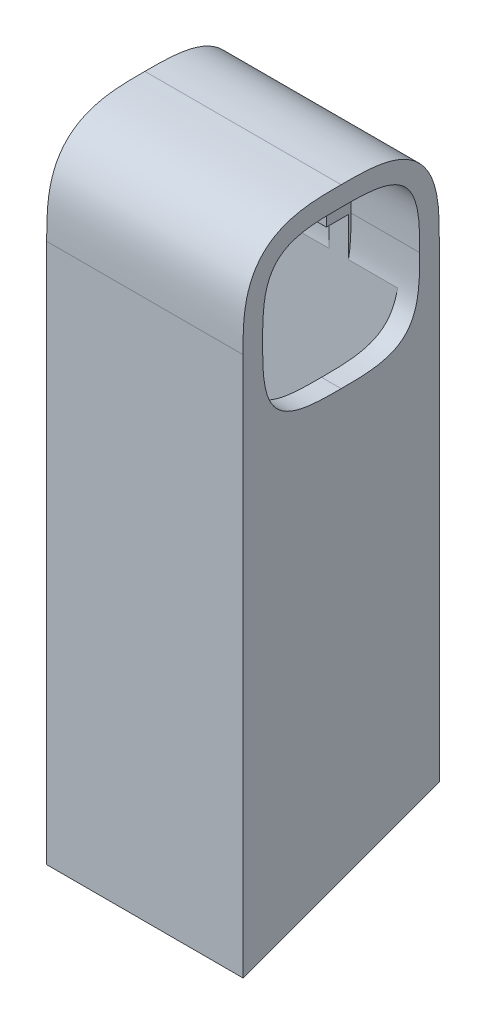
SolidWorks part; units mm, degrees
ref_plane "前视基准面" through (0, 0, 0) normal (0, 0, 1) x (1, 0, 0)
ref_plane "上视基准面" through (0, 0, 0) normal (0, 1, 0) x (1, 0, 0)
ref_plane "右视基准面" through (0, 0, 0) normal (1, 0, 0) x (0, 0, -1)
other "Configuration Table"
sketch "草图1" plane through (0, 0, 0) normal (1, 0, 0) x (0, 0, -1)
  line L4 (0, 0) -> (0, 12.2063) construction
  line L6 (-10, 0) -> (-10, -55)
  line L8 (10, 0) -> (10, -47.7206)
  line L9 (-10, 0) -> (10, 0) construction
  line L10 (-10, -55) -> (10, -47.7206)
  spline S0 degree 4 poles (-1.0181, 10.0032) (-0.7725, 10.0013) (-0.4941, 10.0001) (-0.0263, 9.9999) (0.7234, 10.0003) (1.6031, 9.9942) (2.5936, 9.9522) (3.5304, 9.8651) (4.2846, 9.7393) (4.9221, 9.5926) (5.4228, 9.4446) (5.9166, 9.2643) (6.3946, 9.0487) (6.8546, 8.7957) (7.2712, 8.5176) (7.6286, 8.2324) (7.9468, 7.9356) (8.2427, 7.6166) (8.5281, 7.2568) (8.806, 6.8375) (9.0575, 6.3768) (9.2717, 5.8978) (9.4508, 5.4047) (9.5975, 4.901) (9.7444, 4.2634) (9.8884, 3.3683) (9.9835, 2.2038) (9.9997, 1.1675) (10.0003, 0.3923) (10, 0) knots 0 0 0 0 0 0.048706 0.055984 0.114683 0.173382 0.232082 0.289096 0.318446 0.347795 0.377145 0.406494 0.435844 0.465193 0.494543 0.518534 0.538101 0.562555 0.591905 0.621254 0.650602 0.679953 0.709301 0.738647 0.767998 0.826406 0.91214 1 1 1 1 1 construction
  spline S1 degree 4 poles (0, 10) (0.2475, 10) (0.7583, 10) (1.6031, 9.9942) (2.5936, 9.9522) (3.5304, 9.8651) (4.2846, 9.7393) (4.9221, 9.5926) (5.4228, 9.4446) (5.9166, 9.2643) (6.3946, 9.0487) (6.8546, 8.7957) (7.2712, 8.5176) (7.6286, 8.2324) (7.9468, 7.9356) (8.2427, 7.6166) (8.5281, 7.2568) (8.806, 6.8375) (9.0575, 6.3768) (9.2717, 5.8978) (9.4508, 5.4047) (9.5975, 4.901) (9.7444, 4.2634) (9.8884, 3.3683) (9.9835, 2.2038) (9.9997, 1.1675) (10.0003, 0.3923) (10, 0) knots 0.055984 0.055984 0.055984 0.055984 0.055984 0.114683 0.173382 0.232082 0.289096 0.318446 0.347795 0.377145 0.406494 0.435844 0.465193 0.494543 0.518534 0.538101 0.562555 0.591905 0.621254 0.650602 0.679953 0.709301 0.738647 0.767998 0.826406 0.91214 1 1 1 1 1
  spline S2 degree 4 poles (0, 10) (-0.2475, 10) (-0.7583, 10) (-1.6031, 9.9942) (-2.5936, 9.9522) (-3.5304, 9.8651) (-4.2846, 9.7393) (-4.9221, 9.5926) (-5.4228, 9.4446) (-5.9166, 9.2643) (-6.3946, 9.0487) (-6.8546, 8.7957) (-7.2712, 8.5176) (-7.6286, 8.2324) (-7.9468, 7.9356) (-8.2427, 7.6166) (-8.5281, 7.2568) (-8.806, 6.8375) (-9.0575, 6.3768) (-9.2717, 5.8978) (-9.4508, 5.4047) (-9.5975, 4.901) (-9.7444, 4.2634) (-9.8884, 3.3683) (-9.9835, 2.2038) (-9.9997, 1.1675) (-10.0003, 0.3923) (-10, 0) knots 0.055984 0.055984 0.055984 0.055984 0.055984 0.114683 0.173382 0.232082 0.289096 0.318446 0.347795 0.377145 0.406494 0.435844 0.465193 0.494543 0.518534 0.538101 0.562555 0.591905 0.621254 0.650602 0.679953 0.709301 0.738647 0.767998 0.826406 0.91214 1 1 1 1 1
  dimension "D1" = 20
  dimension "D2" = 55
  dimension "D3" = 70
extrude "凸台-拉伸1" add sketch "草图1" along normal blind 20
sketch "草图4" plane through (0, 0, 0) normal (-1, 0, 0) x (0, 0, 1)
  line L3 (-8, 0.0015) -> (8, 0.0015) construction
  spline S5 degree 3 poles (0, -7.997) (0.1658, -7.997) (0.3341, -7.997) (0.6769, -7.996) (0.8514, -7.995) (1.1985, -7.9913) (1.3702, -7.9885) (1.7022, -7.9803) (1.8625, -7.9748) (2.1776, -7.9606) (2.3333, -7.9517) (2.6457, -7.9296) (2.8024, -7.9164) (3.1102, -7.8854) (3.2605, -7.8675) (3.552, -7.8267) (3.6932, -7.8037) (3.9751, -7.751) (4.1165, -7.7212) (4.3885, -7.6563) (4.5182, -7.6213) (4.7735, -7.5439) (4.8994, -7.5014) (5.1417, -7.4103) (5.2579, -7.3617) (5.8205, -7.1012) (6.203, -6.8395) (6.8426, -6.2) (7.1039, -5.8182) (7.5213, -4.9168) (7.675, -4.3984) (7.885, -3.2682) (7.9421, -2.6571) (7.9993, -1.3734) (8.0005, -0.697) (8, 0.0015) knots 0 0 0 0 0.03125 0.03125 0.0625 0.0625 0.09375 0.09375 0.125 0.125 0.15625 0.15625 0.1875 0.1875 0.21875 0.21875 0.25 0.25 0.28125 0.28125 0.3125 0.3125 0.34375 0.34375 0.375 0.375 0.5 0.5 0.625 0.625 0.75 0.75 0.875 0.875 1 1 1 1
  spline S6 degree 3 poles (-8, 0.0015) (-8.0005, -0.697) (-7.9993, -1.3734) (-7.9421, -2.6571) (-7.885, -3.2682) (-7.675, -4.3984) (-7.5213, -4.9168) (-7.1039, -5.8182) (-6.8426, -6.2) (-6.203, -6.8395) (-5.8205, -7.1012) (-5.2579, -7.3617) (-5.1417, -7.4103) (-4.8994, -7.5014) (-4.7735, -7.5439) (-4.5182, -7.6213) (-4.3885, -7.6563) (-4.1165, -7.7212) (-3.9751, -7.751) (-3.6932, -7.8037) (-3.552, -7.8267) (-3.2605, -7.8675) (-3.1102, -7.8854) (-2.8024, -7.9164) (-2.6457, -7.9296) (-2.3333, -7.9517) (-2.1776, -7.9606) (-1.8625, -7.9748) (-1.7022, -7.9803) (-1.3702, -7.9885) (-1.1985, -7.9913) (-0.8514, -7.995) (-0.6769, -7.996) (-0.3341, -7.997) (-0.1658, -7.997) (0, -7.997) knots 0 0 0 0 0.125 0.125 0.25 0.25 0.375 0.375 0.5 0.5 0.625 0.625 0.65625 0.65625 0.6875 0.6875 0.71875 0.71875 0.75 0.75 0.78125 0.78125 0.8125 0.8125 0.84375 0.84375 0.875 0.875 0.90625 0.90625 0.9375 0.9375 0.96875 0.96875 1 1 1 1
  spline S7 degree 3 poles (-2481.5613, 1693.5931) (21.4601, -3.0504) (-25.7396, 8.0724) (0.6769, 7.999) (0.8514, 7.9981) (1.1985, 7.9943) (1.3702, 7.9915) (1.7022, 7.9833) (1.8625, 7.9779) (2.1776, 7.9636) (2.3333, 7.9547) (2.6457, 7.9327) (2.8024, 7.9195) (3.1102, 7.8884) (3.2605, 7.8706) (3.552, 7.8297) (3.6932, 7.8068) (3.9751, 7.7541) (4.1165, 7.7242) (4.3885, 7.6593) (4.5182, 7.6244) (4.7735, 7.547) (4.8994, 7.5044) (5.1417, 7.4133) (5.2579, 7.3648) (5.8205, 7.1042) (6.203, 6.8426) (6.8426, 6.203) (7.1039, 5.8213) (7.5213, 4.9198) (7.675, 4.4015) (7.885, 3.2713) (7.9421, 2.6601) (9.3673, -29.2877) (-54.4966, -142.6838) (2798.3878, 1095.5016) knots -4.754281 -4.754281 -4.754281 -4.754281 0.03125 0.03125 0.0625 0.0625 0.09375 0.09375 0.125 0.125 0.15625 0.15625 0.1875 0.1875 0.21875 0.21875 0.25 0.25 0.28125 0.28125 0.3125 0.3125 0.34375 0.34375 0.375 0.375 0.5 0.5 0.625 0.625 0.75 0.75 0.875 0.875 6.971761 6.971761 6.971761 6.971761 only from (0, 8) to (8, 0.0015)
  spline S8 degree 3 poles (-2798.4448, 1095.5264) (54.4975, -142.6853) (-9.3673, -29.2879) (-7.9421, 2.6601) (-7.885, 3.2713) (-7.675, 4.4015) (-7.5213, 4.9198) (-7.1039, 5.8213) (-6.8426, 6.203) (-6.203, 6.8426) (-5.8205, 7.1042) (-5.2579, 7.3648) (-5.1417, 7.4133) (-4.8994, 7.5044) (-4.7735, 7.547) (-4.5182, 7.6244) (-4.3885, 7.6593) (-4.1165, 7.7242) (-3.9751, 7.7541) (-3.6932, 7.8068) (-3.552, 7.8297) (-3.2605, 7.8706) (-3.1102, 7.8884) (-2.8024, 7.9195) (-2.6457, 7.9327) (-2.3333, 7.9547) (-2.1776, 7.9636) (-1.8625, 7.9779) (-1.7022, 7.9833) (-1.3702, 7.9915) (-1.1985, 7.9943) (-0.8514, 7.9981) (-0.6769, 7.999) (25.7394, 8.0724) (-21.4594, -3.0503) (2481.5067, 1693.5561) knots -5.971802 -5.971802 -5.971802 -5.971802 0.125 0.125 0.25 0.25 0.375 0.375 0.5 0.5 0.625 0.625 0.65625 0.65625 0.6875 0.6875 0.71875 0.71875 0.75 0.75 0.78125 0.78125 0.8125 0.8125 0.84375 0.84375 0.875 0.875 0.90625 0.90625 0.9375 0.9375 0.96875 0.96875 5.754246 5.754246 5.754246 5.754246 only from (-8, 0.0015) to (0, 8)
  spline S9 degree 3 poles (0, 8) (0.1658, 8) (0.3341, 8) (0.6769, 7.999) (0.8514, 7.9981) (1.1985, 7.9943) (1.3702, 7.9915) (1.7022, 7.9833) (1.8625, 7.9779) (2.1776, 7.9636) (2.3333, 7.9547) (2.6457, 7.9327) (2.8024, 7.9195) (3.1102, 7.8884) (3.2605, 7.8706) (3.552, 7.8297) (3.6932, 7.8068) (3.9751, 7.7541) (4.1165, 7.7242) (4.3885, 7.6593) (4.5182, 7.6244) (4.7735, 7.547) (4.8994, 7.5044) (5.1417, 7.4133) (5.2579, 7.3648) (5.8205, 7.1042) (6.203, 6.8426) (6.8426, 6.203) (7.1039, 5.8213) (7.5213, 4.9198) (7.675, 4.4015) (7.885, 3.2713) (7.9421, 2.6601) (7.9993, 1.3764) (8.0005, 0.7) (8, 0.0015) knots 0 0 0 0 0.03125 0.03125 0.0625 0.0625 0.09375 0.09375 0.125 0.125 0.15625 0.15625 0.1875 0.1875 0.21875 0.21875 0.25 0.25 0.28125 0.28125 0.3125 0.3125 0.34375 0.34375 0.375 0.375 0.5 0.5 0.625 0.625 0.75 0.75 0.875 0.875 1 1 1 1
  spline S10 degree 3 poles (-8, 0.0015) (-8.0005, 0.7) (-7.9993, 1.3764) (-7.9421, 2.6601) (-7.885, 3.2713) (-7.675, 4.4015) (-7.5213, 4.9198) (-7.1039, 5.8213) (-6.8426, 6.203) (-6.203, 6.8426) (-5.8205, 7.1042) (-5.2579, 7.3648) (-5.1417, 7.4133) (-4.8994, 7.5044) (-4.7735, 7.547) (-4.5182, 7.6244) (-4.3885, 7.6593) (-4.1165, 7.7242) (-3.9751, 7.7541) (-3.6932, 7.8068) (-3.552, 7.8297) (-3.2605, 7.8706) (-3.1102, 7.8884) (-2.8024, 7.9195) (-2.6457, 7.9327) (-2.3333, 7.9547) (-2.1776, 7.9636) (-1.8625, 7.9779) (-1.7022, 7.9833) (-1.3702, 7.9915) (-1.1985, 7.9943) (-0.8514, 7.9981) (-0.6769, 7.999) (-0.3341, 8) (-0.1658, 8) (0, 8) knots 0 0 0 0 0.125 0.125 0.25 0.25 0.375 0.375 0.5 0.5 0.625 0.625 0.65625 0.65625 0.6875 0.6875 0.71875 0.71875 0.75 0.75 0.78125 0.78125 0.8125 0.8125 0.84375 0.84375 0.875 0.875 0.90625 0.90625 0.9375 0.9375 0.96875 0.96875 1 1 1 1
  dimension "D1" = 2
extrude "切除-拉伸2" cut sketch "草图4" against normal blind 11
sketch "草图5" plane through (0, -45.3523, -16.5069) normal (0, -0.9397, -0.342) x (1, 0, 0)
  line L0 (20, 28.208) -> (0, 28.208) construction
  line L1 (5.5, 22.708) -> (14.5, 22.708)
  line L2 (5.5, 22.708) -> (5.5, 12.4245)
  line L3 (5.5, 12.4245) -> (14.5, 12.4245)
  line L4 (14.5, 22.708) -> (14.5, 12.4245)
  line L5 (20, 28.208) -> (20, 6.9245) construction
  line L6 (0, 28.208) -> (0, 6.9245) construction
  line L7 (20, 6.9245) -> (0, 6.9245) construction
  dimension "D1" = 5.5
  dimension "D2" = 5.5
  dimension "D3" = 5.5
  dimension "D4" = 5.5
sketch "草图6" plane through (0, 0, 0) normal (-1, 0, 0) x (0, 0, 1)
  line L2 (-0.95, 8.5) -> (-0.95, 7)
  line L3 (-0.95, 7) -> (0.95, 7)
  line L4 (0.95, 8.5) -> (0.95, 7)
  line L5 (-0.95, 8.5) -> (0.95, 7) construction
  line L6 (-0.95, 7) -> (0.95, 8.5) construction
  line L18 (-0.95, 8.5) -> (0.95, 8.5)
  line L19 (8.5, 0.95) -> (8.5, -0.95)
  line L20 (8.5, -0.95) -> (7, -0.95)
  line L21 (7, 0.95) -> (7, -0.95)
  line L22 (8.5, 0.95) -> (7, 0.95)
  line L23 (0.95, -8.5) -> (-0.95, -8.5)
  line L24 (-0.95, -8.5) -> (-0.95, -7)
  line L25 (0.95, -7) -> (-0.95, -7)
  line L26 (0.95, -8.5) -> (0.95, -7)
  line L27 (-8.5, -0.95) -> (-8.5, 0.95)
  line L28 (-8.5, 0.95) -> (-7, 0.95)
  line L29 (-7, -0.95) -> (-7, 0.95)
  line L30 (-8.5, -0.95) -> (-7, -0.95)
  point P0 (0, 7.75)
  point P21 (0, 0)
  dimension "D1" = 1.5
  dimension "D2" = 1.9
  dimension "D4" = 1.5
  dimension "D3" = 4
extrude "凸台-拉伸6" add sketch "草图6" against normal up to surface (11 mm away) up to face at (11, 0.0015, 0)
sketch "草图7" plane through (20, 0, 0) normal (1, 0, 0) x (0, 0, -1)
  line L0 (-8, 0.0015) -> (8, 0.0015) construction
  spline S3 degree 3 poles (0, -7.997) (-0.1658, -7.997) (-0.3341, -7.997) (-0.6769, -7.996) (-0.8514, -7.995) (-1.1985, -7.9913) (-1.3702, -7.9885) (-1.7022, -7.9803) (-1.8625, -7.9748) (-2.1776, -7.9606) (-2.3333, -7.9517) (-2.6457, -7.9296) (-2.8024, -7.9164) (-3.1102, -7.8854) (-3.2605, -7.8675) (-3.552, -7.8267) (-3.6932, -7.8037) (-3.9751, -7.751) (-4.1165, -7.7212) (-4.3885, -7.6563) (-4.5182, -7.6213) (-4.7735, -7.5439) (-4.8994, -7.5014) (-5.1417, -7.4103) (-5.2579, -7.3617) (-5.8205, -7.1012) (-6.203, -6.8395) (-6.8426, -6.2) (-7.1039, -5.8182) (-7.5213, -4.9168) (-7.675, -4.3984) (-7.885, -3.2682) (-7.9421, -2.6571) (-7.9993, -1.3734) (-8.0005, -0.697) (-8, 0.0015) knots 0 0 0 0 0.03125 0.03125 0.0625 0.0625 0.09375 0.09375 0.125 0.125 0.15625 0.15625 0.1875 0.1875 0.21875 0.21875 0.25 0.25 0.28125 0.28125 0.3125 0.3125 0.34375 0.34375 0.375 0.375 0.5 0.5 0.625 0.625 0.75 0.75 0.875 0.875 1 1 1 1
  spline S4 degree 3 poles (8, 0.0015) (8.0005, -0.697) (7.9993, -1.3734) (7.9421, -2.6571) (7.885, -3.2682) (7.675, -4.3984) (7.5213, -4.9168) (7.1039, -5.8182) (6.8426, -6.2) (6.203, -6.8395) (5.8205, -7.1012) (5.2579, -7.3617) (5.1417, -7.4103) (4.8994, -7.5014) (4.7735, -7.5439) (4.5182, -7.6213) (4.3885, -7.6563) (4.1165, -7.7212) (3.9751, -7.751) (3.6932, -7.8037) (3.552, -7.8267) (3.2605, -7.8675) (3.1102, -7.8854) (2.8024, -7.9164) (2.6457, -7.9296) (2.3333, -7.9517) (2.1776, -7.9606) (1.8625, -7.9748) (1.7022, -7.9803) (1.3702, -7.9885) (1.1985, -7.9913) (0.8514, -7.995) (0.6769, -7.996) (0.3341, -7.997) (0.1658, -7.997) (0, -7.997) knots 0 0 0 0 0.125 0.125 0.25 0.25 0.375 0.375 0.5 0.5 0.625 0.625 0.65625 0.65625 0.6875 0.6875 0.71875 0.71875 0.75 0.75 0.78125 0.78125 0.8125 0.8125 0.84375 0.84375 0.875 0.875 0.90625 0.90625 0.9375 0.9375 0.96875 0.96875 1 1 1 1
  spline S5 degree 3 poles (2798.4448, 1095.5264) (-54.4975, -142.6853) (9.3673, -29.2879) (7.9421, 2.6601) (7.885, 3.2713) (7.675, 4.4015) (7.5213, 4.9198) (7.1039, 5.8213) (6.8426, 6.203) (6.203, 6.8426) (5.8205, 7.1042) (5.2579, 7.3648) (5.1417, 7.4133) (4.8994, 7.5044) (4.7735, 7.547) (4.5182, 7.6244) (4.3885, 7.6593) (4.1165, 7.7242) (3.9751, 7.7541) (3.6932, 7.8068) (3.552, 7.8297) (3.2605, 7.8706) (3.1102, 7.8884) (2.8024, 7.9195) (2.6457, 7.9327) (2.3333, 7.9547) (2.1776, 7.9636) (1.8625, 7.9779) (1.7022, 7.9833) (1.3702, 7.9915) (1.1985, 7.9943) (0.8514, 7.9981) (0.6769, 7.999) (-25.7394, 8.0724) (21.4594, -3.0503) (-2481.5067, 1693.5561) knots -5.971802 -5.971802 -5.971802 -5.971802 0.125 0.125 0.25 0.25 0.375 0.375 0.5 0.5 0.625 0.625 0.65625 0.65625 0.6875 0.6875 0.71875 0.71875 0.75 0.75 0.78125 0.78125 0.8125 0.8125 0.84375 0.84375 0.875 0.875 0.90625 0.90625 0.9375 0.9375 0.96875 0.96875 5.754246 5.754246 5.754246 5.754246 only from (8, 0.0015) to (0, 8)
  spline S6 degree 3 poles (2481.5613, 1693.5931) (-21.4601, -3.0504) (25.7396, 8.0724) (-0.6769, 7.999) (-0.8514, 7.9981) (-1.1985, 7.9943) (-1.3702, 7.9915) (-1.7022, 7.9833) (-1.8625, 7.9779) (-2.1776, 7.9636) (-2.3333, 7.9547) (-2.6457, 7.9327) (-2.8024, 7.9195) (-3.1102, 7.8884) (-3.2605, 7.8706) (-3.552, 7.8297) (-3.6932, 7.8068) (-3.9751, 7.7541) (-4.1165, 7.7242) (-4.3885, 7.6593) (-4.5182, 7.6244) (-4.7735, 7.547) (-4.8994, 7.5044) (-5.1417, 7.4133) (-5.2579, 7.3648) (-5.8205, 7.1042) (-6.203, 6.8426) (-6.8426, 6.203) (-7.1039, 5.8213) (-7.5213, 4.9198) (-7.675, 4.4015) (-7.885, 3.2713) (-7.9421, 2.6601) (-9.3673, -29.2877) (54.4966, -142.6838) (-2798.3878, 1095.5016) knots -4.754281 -4.754281 -4.754281 -4.754281 0.03125 0.03125 0.0625 0.0625 0.09375 0.09375 0.125 0.125 0.15625 0.15625 0.1875 0.1875 0.21875 0.21875 0.25 0.25 0.28125 0.28125 0.3125 0.3125 0.34375 0.34375 0.375 0.375 0.5 0.5 0.625 0.625 0.75 0.75 0.875 0.875 6.971761 6.971761 6.971761 6.971761 only from (0, 8) to (-8, 0.0015)
  spline S7 degree 3 poles (8, 0.0015) (8.0005, 0.7) (7.9993, 1.3764) (7.9421, 2.6601) (7.885, 3.2713) (7.675, 4.4015) (7.5213, 4.9198) (7.1039, 5.8213) (6.8426, 6.203) (6.203, 6.8426) (5.8205, 7.1042) (5.2579, 7.3648) (5.1417, 7.4133) (4.8994, 7.5044) (4.7735, 7.547) (4.5182, 7.6244) (4.3885, 7.6593) (4.1165, 7.7242) (3.9751, 7.7541) (3.6932, 7.8068) (3.552, 7.8297) (3.2605, 7.8706) (3.1102, 7.8884) (2.8024, 7.9195) (2.6457, 7.9327) (2.3333, 7.9547) (2.1776, 7.9636) (1.8625, 7.9779) (1.7022, 7.9833) (1.3702, 7.9915) (1.1985, 7.9943) (0.8514, 7.9981) (0.6769, 7.999) (0.3341, 8) (0.1658, 8) (0, 8) knots 0 0 0 0 0.125 0.125 0.25 0.25 0.375 0.375 0.5 0.5 0.625 0.625 0.65625 0.65625 0.6875 0.6875 0.71875 0.71875 0.75 0.75 0.78125 0.78125 0.8125 0.8125 0.84375 0.84375 0.875 0.875 0.90625 0.90625 0.9375 0.9375 0.96875 0.96875 1 1 1 1
  spline S8 degree 3 poles (0, 8) (-0.1658, 8) (-0.3341, 8) (-0.6769, 7.999) (-0.8514, 7.9981) (-1.1985, 7.9943) (-1.3702, 7.9915) (-1.7022, 7.9833) (-1.8625, 7.9779) (-2.1776, 7.9636) (-2.3333, 7.9547) (-2.6457, 7.9327) (-2.8024, 7.9195) (-3.1102, 7.8884) (-3.2605, 7.8706) (-3.552, 7.8297) (-3.6932, 7.8068) (-3.9751, 7.7541) (-4.1165, 7.7242) (-4.3885, 7.6593) (-4.5182, 7.6244) (-4.7735, 7.547) (-4.8994, 7.5044) (-5.1417, 7.4133) (-5.2579, 7.3648) (-5.8205, 7.1042) (-6.203, 6.8426) (-6.8426, 6.203) (-7.1039, 5.8213) (-7.5213, 4.9198) (-7.675, 4.4015) (-7.885, 3.2713) (-7.9421, 2.6601) (-7.9993, 1.3764) (-8.0005, 0.7) (-8, 0.0015) knots 0 0 0 0 0.03125 0.03125 0.0625 0.0625 0.09375 0.09375 0.125 0.125 0.15625 0.15625 0.1875 0.1875 0.21875 0.21875 0.25 0.25 0.28125 0.28125 0.3125 0.3125 0.34375 0.34375 0.375 0.375 0.5 0.5 0.625 0.625 0.75 0.75 0.875 0.875 1 1 1 1
  dimension "D1" = 2
extrude "切除-拉伸3" cut sketch "草图7" against normal offset from surface (7 mm away) 2 up to face at (11, 0.0002, 0)
sketch "草图8" plane through (13, 0, 0) normal (1, 0, 0) x (0, 0, -1)
  spline S8 degree 3 poles (71.1656, -3003.6534) (-63.9407, 33.71) (-30.2544, -6.0097) (1.6326, -5.4835) (2.0401, -5.4694) (2.8532, -5.4043) (3.2612, -5.3542) (3.8609, -5.2124) (4.059, -5.1531) (4.3424, -5.0328) (4.4342, -4.9875) (4.6088, -4.8798) (4.6921, -4.8164) (4.9061, -4.5977) (5.0067, -4.4126) (5.1626, -4.0354) (5.2207, -3.8371) (5.3605, -3.241) (5.4087, -2.8388) (5.4729, -2.031) (5.4864, -1.625) (6.0333, 30.4896) (-35.4421, 62.4262) (3003.5864, 77.6068) knots -9.52038 -9.52038 -9.52038 -9.52038 0.125 0.125 0.25 0.25 0.375 0.375 0.4375 0.4375 0.46875 0.46875 0.5 0.5 0.5625 0.5625 0.625 0.625 0.75 0.75 0.875 0.875 10.622375 10.622375 10.622375 10.622375 only from (0, -5.497) to (5.5, 0.0015)
  spline S9 degree 3 poles (3003.6455, 70.6834) (-35.6, -64.4893) (6.0376, -30.4733) (5.4863, 1.6344) (5.4726, 2.042) (5.4073, 2.8552) (5.3577, 3.2635) (5.2144, 3.8628) (5.1553, 4.0609) (5.035, 4.3443) (4.9896, 4.436) (4.8818, 4.6105) (4.8181, 4.6936) (4.5991, 4.9071) (4.414, 5.0075) (4.0367, 5.1634) (3.8385, 5.2215) (3.2422, 5.36) (2.8401, 5.4087) (2.0323, 5.4727) (1.6265, 5.4867) (-30.2714, 6.0088) (-62.1867, -33.5593) (-53.4926, 3004.0512) knots -9.586615 -9.586615 -9.586615 -9.586615 0.125 0.125 0.25 0.25 0.375 0.375 0.4375 0.4375 0.46875 0.46875 0.5 0.5 0.5625 0.5625 0.625 0.625 0.75 0.75 0.875 0.875 10.556434 10.556434 10.556434 10.556434 only from (5.5, 0.0015) to (0, 5.5)
  spline S10 degree 3 poles (-71.1656, 3003.6564) (63.9407, -33.7069) (30.2544, 6.0127) (-1.6326, 5.4866) (-2.0401, 5.4724) (-2.8532, 5.4074) (-3.2612, 5.3572) (-3.8609, 5.2154) (-4.059, 5.1561) (-4.3424, 5.0359) (-4.4342, 4.9905) (-4.6088, 4.8829) (-4.6921, 4.8194) (-4.9061, 4.6008) (-5.0067, 4.4157) (-5.1626, 4.0384) (-5.2207, 3.8402) (-5.3605, 3.2441) (-5.4087, 2.8419) (-5.4729, 2.034) (-5.4864, 1.6281) (-6.0333, -30.4866) (35.4421, -62.4231) (-3003.5864, -77.6038) knots -9.52038 -9.52038 -9.52038 -9.52038 0.125 0.125 0.25 0.25 0.375 0.375 0.4375 0.4375 0.46875 0.46875 0.5 0.5 0.5625 0.5625 0.625 0.625 0.75 0.75 0.875 0.875 10.622375 10.622375 10.622375 10.622375 only from (0, 5.5) to (-5.5, 0.0015)
  spline S11 degree 3 poles (-3003.6455, -70.6803) (35.6, 64.4923) (-6.0376, 30.4763) (-5.4863, -1.6313) (-5.4726, -2.039) (-5.4073, -2.8522) (-5.3577, -3.2605) (-5.2144, -3.8598) (-5.1553, -4.0579) (-5.035, -4.3412) (-4.9896, -4.4329) (-4.8818, -4.6074) (-4.8181, -4.6906) (-4.5991, -4.9041) (-4.414, -5.0045) (-4.0367, -5.1603) (-3.8385, -5.2185) (-3.2422, -5.3569) (-2.8401, -5.4057) (-2.0323, -5.4697) (-1.6265, -5.4837) (30.2714, -6.0057) (62.1867, 33.5623) (53.4926, -3004.0482) knots -9.586615 -9.586615 -9.586615 -9.586615 0.125 0.125 0.25 0.25 0.375 0.375 0.4375 0.4375 0.46875 0.46875 0.5 0.5 0.5625 0.5625 0.625 0.625 0.75 0.75 0.875 0.875 10.556434 10.556434 10.556434 10.556434 only from (-5.5, 0.0015) to (0, -5.497)
  spline S12 degree 3 poles (0, -5.497) (0.4083, -5.497) (0.8166, -5.497) (1.6326, -5.4835) (2.0401, -5.4694) (2.8532, -5.4043) (3.2612, -5.3542) (3.8609, -5.2124) (4.059, -5.1531) (4.3424, -5.0328) (4.4342, -4.9875) (4.6088, -4.8798) (4.6921, -4.8164) (4.9061, -4.5977) (5.0067, -4.4126) (5.1626, -4.0354) (5.2207, -3.8371) (5.3605, -3.241) (5.4087, -2.8388) (5.4729, -2.031) (5.4864, -1.625) (5.5003, -0.8118) (5.5003, -0.4051) (5.5, 0.0015) knots 0 0 0 0 0.125 0.125 0.25 0.25 0.375 0.375 0.4375 0.4375 0.46875 0.46875 0.5 0.5 0.5625 0.5625 0.625 0.625 0.75 0.75 0.875 0.875 1 1 1 1
  spline S13 degree 3 poles (5.5, 0.0015) (5.5003, 0.4099) (5.5003, 0.8183) (5.4863, 1.6344) (5.4726, 2.042) (5.4073, 2.8552) (5.3577, 3.2635) (5.2144, 3.8628) (5.1553, 4.0609) (5.035, 4.3443) (4.9896, 4.436) (4.8818, 4.6105) (4.8181, 4.6936) (4.5991, 4.9071) (4.414, 5.0075) (4.0367, 5.1634) (3.8385, 5.2215) (3.2422, 5.36) (2.8401, 5.4087) (2.0323, 5.4727) (1.6265, 5.4867) (0.8133, 5.5) (0.4066, 5.5) (0, 5.5) knots 0 0 0 0 0.125 0.125 0.25 0.25 0.375 0.375 0.4375 0.4375 0.46875 0.46875 0.5 0.5 0.5625 0.5625 0.625 0.625 0.75 0.75 0.875 0.875 1 1 1 1
  spline S14 degree 3 poles (0, 5.5) (-0.4083, 5.5) (-0.8166, 5.5) (-1.6326, 5.4866) (-2.0401, 5.4724) (-2.8532, 5.4074) (-3.2612, 5.3572) (-3.8609, 5.2154) (-4.059, 5.1561) (-4.3424, 5.0359) (-4.4342, 4.9905) (-4.6088, 4.8829) (-4.6921, 4.8194) (-4.9061, 4.6008) (-5.0067, 4.4157) (-5.1626, 4.0384) (-5.2207, 3.8402) (-5.3605, 3.2441) (-5.4087, 2.8419) (-5.4729, 2.034) (-5.4864, 1.6281) (-5.5003, 0.8148) (-5.5003, 0.4082) (-5.5, 0.0015) knots 0 0 0 0 0.125 0.125 0.25 0.25 0.375 0.375 0.4375 0.4375 0.46875 0.46875 0.5 0.5 0.5625 0.5625 0.625 0.625 0.75 0.75 0.875 0.875 1 1 1 1
  spline S15 degree 3 poles (-5.5, 0.0015) (-5.5003, -0.4069) (-5.5003, -0.8153) (-5.4863, -1.6313) (-5.4726, -2.039) (-5.4073, -2.8522) (-5.3577, -3.2605) (-5.2144, -3.8598) (-5.1553, -4.0579) (-5.035, -4.3412) (-4.9896, -4.4329) (-4.8818, -4.6074) (-4.8181, -4.6906) (-4.5991, -4.9041) (-4.414, -5.0045) (-4.0367, -5.1603) (-3.8385, -5.2185) (-3.2422, -5.3569) (-2.8401, -5.4057) (-2.0323, -5.4697) (-1.6265, -5.4837) (-0.8133, -5.497) (-0.4066, -5.497) (0, -5.497) knots 0 0 0 0 0.125 0.125 0.25 0.25 0.375 0.375 0.4375 0.4375 0.46875 0.46875 0.5 0.5 0.5625 0.5625 0.625 0.625 0.75 0.75 0.875 0.875 1 1 1 1
  dimension "D1" = 2.5
extrude "切除-拉伸4" cut sketch "草图8" against normal up to next
sketch "草图9" plane through (0, 0, 0) normal (0, 1, 0) x (1, 0, 0)
  line L0 (20, 0) -> (0, 0) construction
  line L1 (2, 7.7501) -> (18, 7.7501)
  line L2 (2, 7.7501) -> (2, -7.7501)
  line L3 (2, -7.7501) -> (18, -7.7501)
  line L4 (18, 7.7501) -> (18, -7.7501)
  line L5 (2, 7.7501) -> (18, -7.7501) construction
  line L6 (2, -7.7501) -> (18, 7.7501) construction
  line L7 (20, 10.0001) -> (0, 10.0001) construction
  line L8 (20, 0) -> (20, 10.0001) construction
  point P0 (10, 0)
  dimension "D1" = 2.25
  dimension "D2" = 2
extrude "切除-拉伸5" cut sketch "草图9" against normal through all
sketch "草图10" plane through (0, 0, 0) normal (-1, 0, 0) x (0, 0, 1)
  line L0 (-10, 0) -> (10, 0) construction
  spline S0 degree 4 poles (-1999.7762, 35.8258) (71.2799, 14.8233) (-13.0609, 9.1133) (-2.9412, 10.187) (2.5936, 9.9522) (3.5304, 9.8651) (4.2846, 9.7393) (4.9221, 9.5926) (5.4228, 9.4446) (5.9166, 9.2643) (6.3946, 9.0487) (6.8546, 8.7957) (7.2712, 8.5176) (7.6286, 8.2324) (7.9468, 7.9356) (8.2427, 7.6166) (8.5281, 7.2568) (8.806, 6.8375) (9.0575, 6.3768) (9.2717, 5.8978) (9.4508, 5.4047) (9.5975, 4.901) (9.7444, 4.2634) (9.8884, 3.3683) (11.2277, -13.0391) (-4.3334, -29.916) (199.8515, -33.8775) (-1904.7195, -573.6159) knots -1.01347 -1.01347 -1.01347 -1.01347 -1.01347 0.114683 0.173382 0.232082 0.289096 0.318446 0.347795 0.377145 0.406494 0.435844 0.465193 0.494543 0.518534 0.538101 0.562555 0.591905 0.621254 0.650602 0.679953 0.709301 0.738647 0.767998 0.826406 0.91214 4.420778 4.420778 4.420778 4.420778 4.420778 only from (0, 10) to (10, 0) construction
  spline S1 degree 4 poles (1904.696, -573.6099) (-199.8499, -33.8775) (4.3334, -29.9159) (-11.2277, -13.039) (-9.8884, 3.3683) (-9.7444, 4.2634) (-9.5975, 4.901) (-9.4508, 5.4047) (-9.2717, 5.8978) (-9.0575, 6.3768) (-8.806, 6.8375) (-8.5281, 7.2568) (-8.2427, 7.6166) (-7.9468, 7.9356) (-7.6286, 8.2324) (-7.2712, 8.5176) (-6.8546, 8.7957) (-6.3946, 9.0487) (-5.9166, 9.2643) (-5.4228, 9.4446) (-4.9221, 9.5926) (-4.2846, 9.7393) (-3.5304, 9.8651) (-2.5936, 9.9522) (2.9412, 10.187) (13.0609, 9.1133) (-71.2793, 14.8233) (1999.7535, 35.8256) knots -3.364784 -3.364784 -3.364784 -3.364784 -3.364784 0.143843 0.229578 0.287985 0.317337 0.346683 0.376031 0.405381 0.43473 0.464079 0.493429 0.517883 0.53745 0.561441 0.59079 0.62014 0.649489 0.678839 0.708189 0.737538 0.766888 0.823902 0.882601 0.941301 2.06945 2.06945 2.06945 2.06945 2.06945 only from (-10, 0) to (0, 10) construction
  spline S2 degree 4 poles (0, 10) (0.2475, 10) (0.7583, 10) (1.6031, 9.9942) (2.5936, 9.9522) (3.5304, 9.8651) (4.2846, 9.7393) (4.9221, 9.5926) (5.4228, 9.4446) (5.9166, 9.2643) (6.3946, 9.0487) (6.8546, 8.7957) (7.2712, 8.5176) (7.6286, 8.2324) (7.9468, 7.9356) (8.2427, 7.6166) (8.5281, 7.2568) (8.806, 6.8375) (9.0575, 6.3768) (9.2717, 5.8978) (9.4508, 5.4047) (9.5975, 4.901) (9.7444, 4.2634) (9.8884, 3.3683) (9.9835, 2.2038) (9.9997, 1.1675) (10.0003, 0.3923) (10, 0) knots 0.055984 0.055984 0.055984 0.055984 0.055984 0.114683 0.173382 0.232082 0.289096 0.318446 0.347795 0.377145 0.406494 0.435844 0.465193 0.494543 0.518534 0.538101 0.562555 0.591905 0.621254 0.650602 0.679953 0.709301 0.738647 0.767998 0.826406 0.91214 1 1 1 1 1 construction
  spline S3 degree 4 poles (-10, 0) (-10.0003, 0.3923) (-9.9997, 1.1675) (-9.9835, 2.2038) (-9.8884, 3.3683) (-9.7444, 4.2634) (-9.5975, 4.901) (-9.4508, 5.4047) (-9.2717, 5.8978) (-9.0575, 6.3768) (-8.806, 6.8375) (-8.5281, 7.2568) (-8.2427, 7.6166) (-7.9468, 7.9356) (-7.6286, 8.2324) (-7.2712, 8.5176) (-6.8546, 8.7957) (-6.3946, 9.0487) (-5.9166, 9.2643) (-5.4228, 9.4446) (-4.9221, 9.5926) (-4.2846, 9.7393) (-3.5304, 9.8651) (-2.5936, 9.9522) (-1.6031, 9.9942) (-0.7583, 10) (-0.2475, 10) (0, 10) knots 0.055984 0.055984 0.055984 0.055984 0.055984 0.143843 0.229578 0.287985 0.317337 0.346683 0.376031 0.405381 0.43473 0.464079 0.493429 0.517883 0.53745 0.561441 0.59079 0.62014 0.649489 0.678839 0.708189 0.737538 0.766888 0.823902 0.882601 0.941301 1 1 1 1 1 construction
  spline S4 degree 4 poles (-10, 0) (-10.0003, -0.3923) (-9.9997, -1.1675) (-9.9835, -2.2038) (-9.8884, -3.3683) (-9.7444, -4.2634) (-9.5975, -4.901) (-9.4508, -5.4047) (-9.2717, -5.8978) (-9.0575, -6.3768) (-8.806, -6.8375) (-8.5281, -7.2568) (-8.2427, -7.6166) (-7.9468, -7.9356) (-7.6286, -8.2324) (-7.2712, -8.5176) (-6.8546, -8.7957) (-6.3946, -9.0487) (-5.9166, -9.2643) (-5.4228, -9.4446) (-4.9221, -9.5926) (-4.2846, -9.7393) (-3.5304, -9.8651) (-2.5936, -9.9522) (-1.6031, -9.9942) (-0.7583, -10) (-0.2475, -10) (0, -10) knots 0.055984 0.055984 0.055984 0.055984 0.055984 0.143843 0.229578 0.287985 0.317337 0.346683 0.376031 0.405381 0.43473 0.464079 0.493429 0.517883 0.53745 0.561441 0.59079 0.62014 0.649489 0.678839 0.708189 0.737538 0.766888 0.823902 0.882601 0.941301 1 1 1 1 1 construction
  spline S5 degree 4 poles (0, -10) (0.2475, -10) (0.7583, -10) (1.6031, -9.9942) (2.5936, -9.9522) (3.5304, -9.8651) (4.2846, -9.7393) (4.9221, -9.5926) (5.4228, -9.4446) (5.9166, -9.2643) (6.3946, -9.0487) (6.8546, -8.7957) (7.2712, -8.5176) (7.6286, -8.2324) (7.9468, -7.9356) (8.2427, -7.6166) (8.5281, -7.2568) (8.806, -6.8375) (9.0575, -6.3768) (9.2717, -5.8978) (9.4508, -5.4047) (9.5975, -4.901) (9.7444, -4.2634) (9.8884, -3.3683) (9.9835, -2.2038) (9.9997, -1.1675) (10.0003, -0.3923) (10, 0) knots 0.055984 0.055984 0.055984 0.055984 0.055984 0.114683 0.173382 0.232082 0.289096 0.318446 0.347795 0.377145 0.406494 0.435844 0.465193 0.494543 0.518534 0.538101 0.562555 0.591905 0.621254 0.650602 0.679953 0.709301 0.738647 0.767998 0.826406 0.91214 1 1 1 1 1 construction
  spline S6 degree 1 poles (-8.5, 0) (0, -8.5) knots 0 0 1 1 construction
  spline S7 degree 1 poles (0, -8.5) (8.5, 0) knots 0 0 1 1 construction
  spline S8 degree 1 poles (0, 8.5) (8.5, 0) knots 0 0 1 1 construction
  spline S9 degree 1 poles (-8.5, 0) (0, 8.5) knots 0 0 1 1 construction
  spline S10 degree 3 poles (-8.5, 0) (-8.5005, -0.6799) (-8.4988, -2.0733) (-8.3249, -3.9613) (-7.8322, -5.6436) (-6.9456, -6.9453) (-5.6453, -7.8317) (-3.9583, -8.3251) (-2.0792, -8.4989) (-0.681, -8.5) (0, -8.5) knots 0.05592 0.05592 0.05592 0.05592 0.17393 0.29194 0.40995 0.52796 0.64597 0.76398 0.88199 1 1 1 1
  spline S11 degree 3 poles (0, -8.5) (0.681, -8.5) (2.0792, -8.4989) (3.9583, -8.3251) (5.6453, -7.8317) (6.9456, -6.9453) (7.8322, -5.6436) (8.3249, -3.9613) (8.4988, -2.0733) (8.5005, -0.6799) (8.5, 0) knots 0.055984 0.055984 0.055984 0.055984 0.173994 0.292004 0.410014 0.528024 0.646034 0.764044 0.882054 1.000064 1.000064 1.000064 1.000064
  spline S12 degree 3 poles (8.5, 0) (8.5005, 0.6799) (8.4988, 2.0733) (8.3249, 3.9613) (7.8322, 5.6436) (6.9456, 6.9453) (5.6453, 7.8317) (3.9583, 8.3251) (2.0792, 8.4989) (0.681, 8.5) (0, 8.5) knots 0.055984 0.055984 0.055984 0.055984 0.173994 0.292004 0.410014 0.528024 0.646034 0.764044 0.882054 1.000064 1.000064 1.000064 1.000064
  spline S13 degree 3 poles (0, 8.5) (-0.681, 8.5) (-2.0792, 8.4989) (-3.9583, 8.3251) (-5.6453, 7.8317) (-6.9456, 6.9453) (-7.8322, 5.6436) (-8.3249, 3.9613) (-8.4988, 2.0733) (-8.5005, 0.6799) (-8.5, 0) knots 0.05592 0.05592 0.05592 0.05592 0.17393 0.29194 0.40995 0.52796 0.64597 0.76398 0.88199 1 1 1 1
  dimension "D1" = 1.5
ref_plane "基准面1" through (5, 0, 0) normal (-1, 0, 0) x (0, 0, 1)
sketch "草图11" plane through (5, 0, 0) normal (-1, 0, 0) x (0, 0, 1)
  spline S0 degree 3 poles (1774.558, -930.7011) (-81.3106, 20.8722) (-17.9679, -10.3534) (3.9583, -8.3251) (5.6453, -7.8317) (6.9456, -6.9453) (7.8322, -5.6436) (8.3249, -3.9613) (10.3984, 18.5437) (-22.1005, 81.102) (960.1166, -1758.9576) knots -3.720989 -3.720989 -3.720989 -3.720989 0.173994 0.292004 0.410014 0.528024 0.646034 0.764044 0.882054 4.866117 4.866117 4.866117 4.866117 only from (0, -8.5) to (8.5, 0) construction
  spline S1 degree 3 poles (960.1424, 1759.0059) (-22.101, -81.1031) (10.3984, -18.5439) (8.3249, 3.9613) (7.8322, 5.6436) (6.9456, 6.9453) (5.6453, 7.8317) (3.9583, 8.3251) (-17.9681, 10.3534) (-81.3116, -20.8727) (1774.6006, 930.723) knots -3.810104 -3.810104 -3.810104 -3.810104 0.173994 0.292004 0.410014 0.528024 0.646034 0.764044 0.882054 4.777067 4.777067 4.777067 4.777067 only from (8.5, 0) to (0, 8.5) construction
  spline S2 degree 3 poles (-1774.558, 930.7011) (81.3106, -20.8722) (17.9679, 10.3534) (-3.9583, 8.3251) (-5.6453, 7.8317) (-6.9456, 6.9453) (-7.8322, 5.6436) (-8.3249, 3.9613) (-10.3984, -18.5437) (22.1005, -81.102) (-960.1166, 1758.9576) knots -3.721053 -3.721053 -3.721053 -3.721053 0.17393 0.29194 0.40995 0.52796 0.64597 0.76398 0.88199 4.866053 4.866053 4.866053 4.866053 only from (0, 8.5) to (-8.5, 0) construction
  spline S3 degree 3 poles (-960.1424, -1759.0059) (22.101, 81.1031) (-10.3984, 18.5439) (-8.3249, -3.9613) (-7.8322, -5.6436) (-6.9456, -6.9453) (-5.6453, -7.8317) (-3.9583, -8.3251) (17.9681, -10.3534) (81.3116, 20.8727) (-1774.6006, -930.723) knots -3.810168 -3.810168 -3.810168 -3.810168 0.17393 0.29194 0.40995 0.52796 0.64597 0.76398 0.88199 4.777003 4.777003 4.777003 4.777003 only from (-8.5, 0) to (0, -8.5) construction
  spline S4 degree 3 poles (0, -8.5) (0.681, -8.5) (2.0792, -8.4989) (3.9583, -8.3251) (5.6453, -7.8317) (6.9456, -6.9453) (7.8322, -5.6436) (8.3249, -3.9613) (8.4988, -2.0733) (8.5005, -0.6799) (8.5, 0) knots 0.055984 0.055984 0.055984 0.055984 0.173994 0.292004 0.410014 0.528024 0.646034 0.764044 0.882054 1.000064 1.000064 1.000064 1.000064
  spline S5 degree 3 poles (8.5, 0) (8.5005, 0.6799) (8.4988, 2.0733) (8.3249, 3.9613) (7.8322, 5.6436) (6.9456, 6.9453) (5.6453, 7.8317) (3.9583, 8.3251) (2.0792, 8.4989) (0.681, 8.5) (0, 8.5) knots 0.055984 0.055984 0.055984 0.055984 0.173994 0.292004 0.410014 0.528024 0.646034 0.764044 0.882054 1.000064 1.000064 1.000064 1.000064
  spline S6 degree 3 poles (0, 8.5) (-0.681, 8.5) (-2.0792, 8.4989) (-3.9583, 8.3251) (-5.6453, 7.8317) (-6.9456, 6.9453) (-7.8322, 5.6436) (-8.3249, 3.9613) (-8.4988, 2.0733) (-8.5005, 0.6799) (-8.5, 0) knots 0.05592 0.05592 0.05592 0.05592 0.17393 0.29194 0.40995 0.52796 0.64597 0.76398 0.88199 1 1 1 1
  spline S7 degree 3 poles (-8.5, 0) (-8.5005, -0.6799) (-8.4988, -2.0733) (-8.3249, -3.9613) (-7.8322, -5.6436) (-6.9456, -6.9453) (-5.6453, -7.8317) (-3.9583, -8.3251) (-2.0792, -8.4989) (-0.681, -8.5) (0, -8.5) knots 0.05592 0.05592 0.05592 0.05592 0.17393 0.29194 0.40995 0.52796 0.64597 0.76398 0.88199 1 1 1 1
extrude "切除-拉伸8" cut sketch "草图11" against normal blind 1.5
